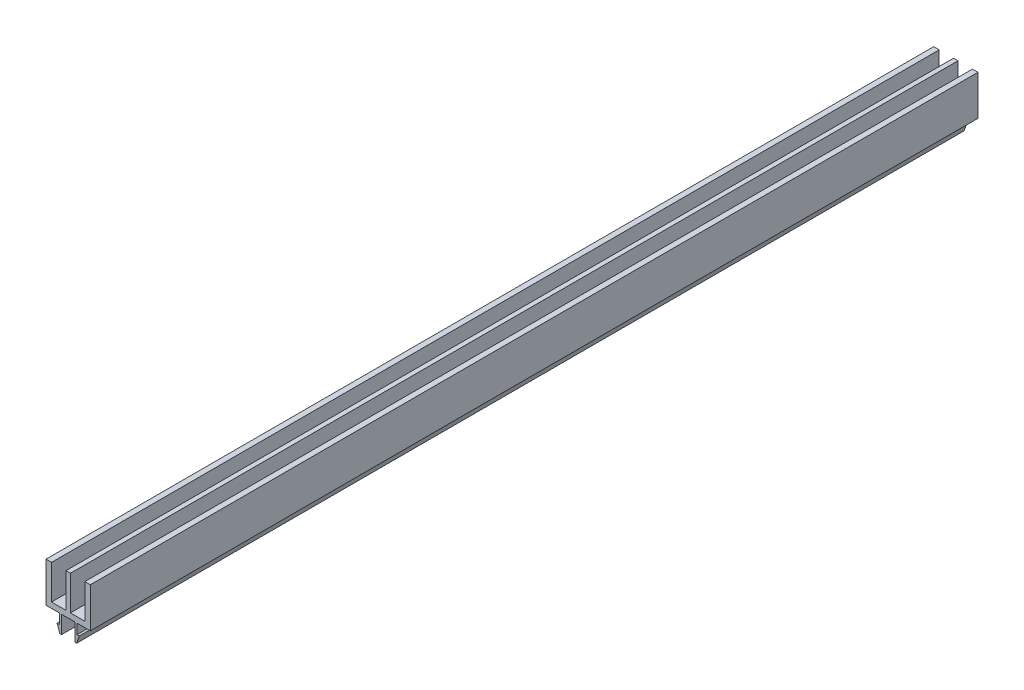
SolidWorks part; units mm, degrees
ref_plane "Plan de face" through (0, 0, 0) normal (0, 0, 1) x (1, 0, 0)
ref_plane "Plan de dessus" through (0, 0, 0) normal (0, 1, 0) x (1, 0, 0)
ref_plane "Plan de droite" through (0, 0, 0) normal (1, 0, 0) x (0, 0, -1)
ref_plane "Plan1" through (0, 0, 50) normal (0, 0, 1) x (1, 0, 0)
sketch "Esquisse1" plane through (0, 0, 50) normal (0, 0, 1) x (1, 0, 0)
  line L0 (-1, 2.5) -> (-7.5, 2.5)
  line L1 (-7.5, 2.5) -> (-7.5, 18)
  line L2 (-7.5, 18) -> (-10, 18)
  line L3 (-10, 18) -> (-10, 0)
  line L4 (-10, 0) -> (-4, 0)
  line L5 (-4, 0) -> (-4, -4.5)
  line L6 (-4, -4.5) -> (-5, -4.5)
  line L7 (-5, -4.5) -> (-3.75, -8)
  line L8 (-3.75, -8) -> (-3, -8)
  line L9 (-3, -8) -> (-3, 0)
  line L10 (-3, 0) -> (3, 0)
  line L11 (3, 0) -> (3, -8)
  line L12 (3, -8) -> (3.75, -8)
  line L13 (3.75, -8) -> (5, -4.5)
  line L14 (5, -4.5) -> (4, -4.5)
  line L15 (4, -4.5) -> (4, 0)
  line L16 (4, 0) -> (10, 0)
  line L17 (10, 0) -> (10, 18)
  line L18 (10, 18) -> (7.5, 18)
  line L19 (7.5, 18) -> (7.5, 2.5)
  line L20 (7.5, 2.5) -> (1, 2.5)
  line L21 (1, 2.5) -> (1, 18)
  line L22 (1, 18) -> (-1, 18)
  line L23 (-1, 18) -> (-1, 2.5)
extrude "Boss.-Extru.1" add sketch "Esquisse1" against normal blind 400.29
